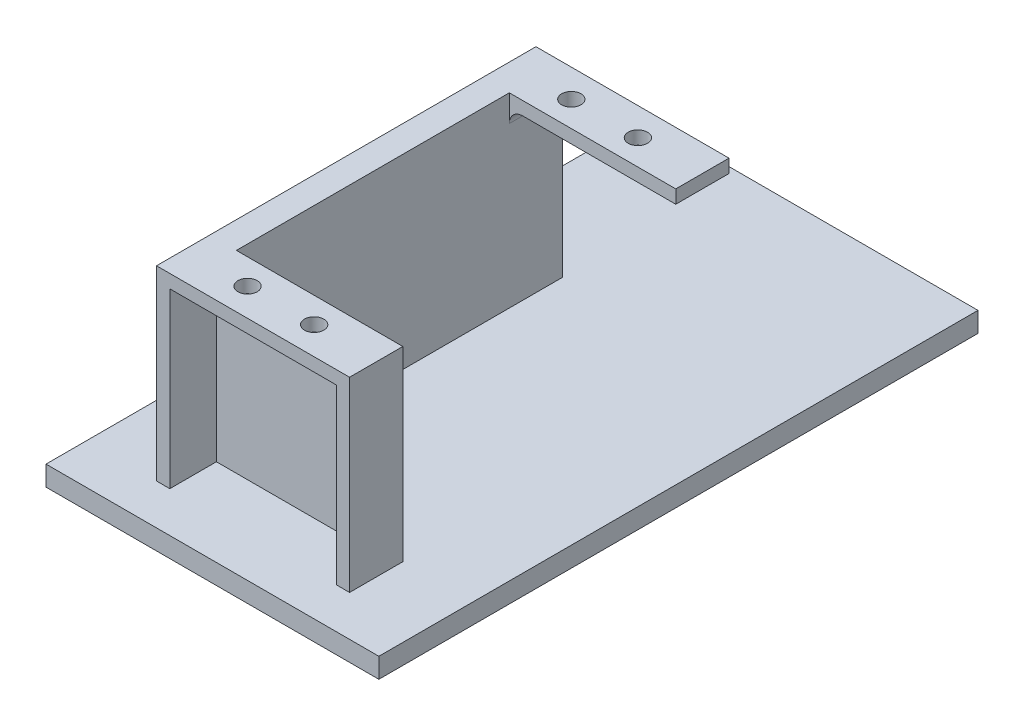
SolidWorks part; units mm, degrees
ref_plane "정면" through (0, 0, 0) normal (0, 0, 1) x (1, 0, 0)
ref_plane "윗면" through (0, 0, 0) normal (0, 1, 0) x (1, 0, 0)
ref_plane "우측면" through (0, 0, 0) normal (1, 0, 0) x (0, 0, -1)
sketch "스케치1" plane through (0, 0, 0) normal (0, 1, 0) x (1, 0, 0)
  line L0 (0, 0) -> (0, 28.5) construction
  line L1 (-10.5, -20.5) -> (10.5, -20.5)
  line L2 (-10.5, -20.5) -> (-10.5, 20.5)
  line L3 (-10.5, 20.5) -> (10.5, 20.5)
  line L4 (10.5, -20.5) -> (10.5, 20.5)
  line L5 (-10.5, -20.5) -> (10.5, 20.5) construction
  line L6 (-10.5, 20.5) -> (10.5, -20.5) construction
  line L7 (-14.5, 28.5) -> (14.5, 28.5)
  line L8 (-14.5, 28.5) -> (-14.5, -28.5)
  line L9 (-14.5, -28.5) -> (14.5, -28.5)
  line L10 (14.5, 28.5) -> (14.5, -28.5)
  line L11 (-14.5, 28.5) -> (14.5, -28.5) construction
  line L12 (-14.5, -28.5) -> (14.5, 28.5) construction
  circle A0 centre (-5, 24.31) radius 1.45
  circle A1 centre (-5, -24.32) radius 1.45
  circle A2 centre (5, -24.32) radius 1.45
  circle A3 centre (5, 24.31) radius 1.45
  point P0 (0, 0)
  point P5 (0, 10.4)
  point P9 (0, 0)
  dimension "D6" = 2.9
  dimension "D8" = 48.63
  dimension "D1" = 41
  dimension "D2" = 21
  dimension "D3" = 10.1
  dimension "D4" = 8
  dimension "D5" = 4
  dimension "D7" = 10
  dimension "D9" = 13.91
extrude "보스-돌출1" add sketch "스케치1" along normal blind 28
sketch "스케치2" plane through (-14, 0, 28.5) normal (0, 0, -1) x (-1, 0, 0)
  line L2 (-26.5, 26) -> (-1.5, 26)
  line L3 (-26.5, 26) -> (-26.5, 0)
  line L4 (-26.5, 0) -> (-1.5, 0)
  line L5 (-1.5, 26) -> (-1.5, 0)
  line L7 (0.5, 28) -> (-28.5, 28) construction
  line L8 (0.5, 28) -> (0.5, 0) construction
  line L9 (-28.5, 28) -> (-28.5, 0) construction
  line L10 (0.5, 0) -> (-28.5, 0) construction
  dimension "D1" = 2
  dimension "D2" = 2
  dimension "D3" = 2
extrude "컷-돌출1" cut sketch "스케치2" along normal blind 7
sketch "스케치3" plane through (14.5, 0, 0) normal (1, 0, 0) x (0, 0, -1)
  line L0 (28.5, 28) -> (28.5, 0) construction
  line L1 (28.5, 26) -> (-20.5, 26)
  line L2 (28.5, 26) -> (28.5, 0)
  line L3 (28.5, 0) -> (-20.5, 0)
  line L4 (-20.5, 26) -> (-20.5, 0)
  line L5 (-28.5, 0) -> (28.5, 0) construction
  line L6 (-20.5, 28) -> (-20.5, 0) construction
extrude "컷-돌출2" cut sketch "스케치3" against normal blind 25
sketch "스케치4" plane through (0, 28, 0) normal (0, 1, 0) x (1, 0, 0)
  line L1 (10.5, 20.5) -> (14.5, 20.5)
  line L2 (10.5, 20.5) -> (10.5, -20.5)
  line L3 (10.5, -20.5) -> (14.5, -20.5)
  line L4 (14.5, 20.5) -> (14.5, -20.5)
extrude "컷-돌출3" cut sketch "스케치4" against normal blind 25
fillet "필렛1" radius 2 1 edges at (-10.5, 26, -24.5)
sketch "스케치5" plane through (0, 0, 0) normal (0, -1, 0) x (1, 0, 0)
  line L1 (-25, 34.6) -> (25, 34.6)
  line L2 (-25, 34.6) -> (-25, -55.4)
  line L3 (-25, -55.4) -> (25, -55.4)
  line L4 (25, 34.6) -> (25, -55.4)
  line L5 (-25, 34.6) -> (25, -55.4) construction
  line L6 (-25, -55.4) -> (25, 34.6) construction
  point P0 (0, -10.4)
  dimension "D1" = 45
  dimension "D2" = 25
extrude "보스-돌출2" add sketch "스케치5" along normal blind 3
